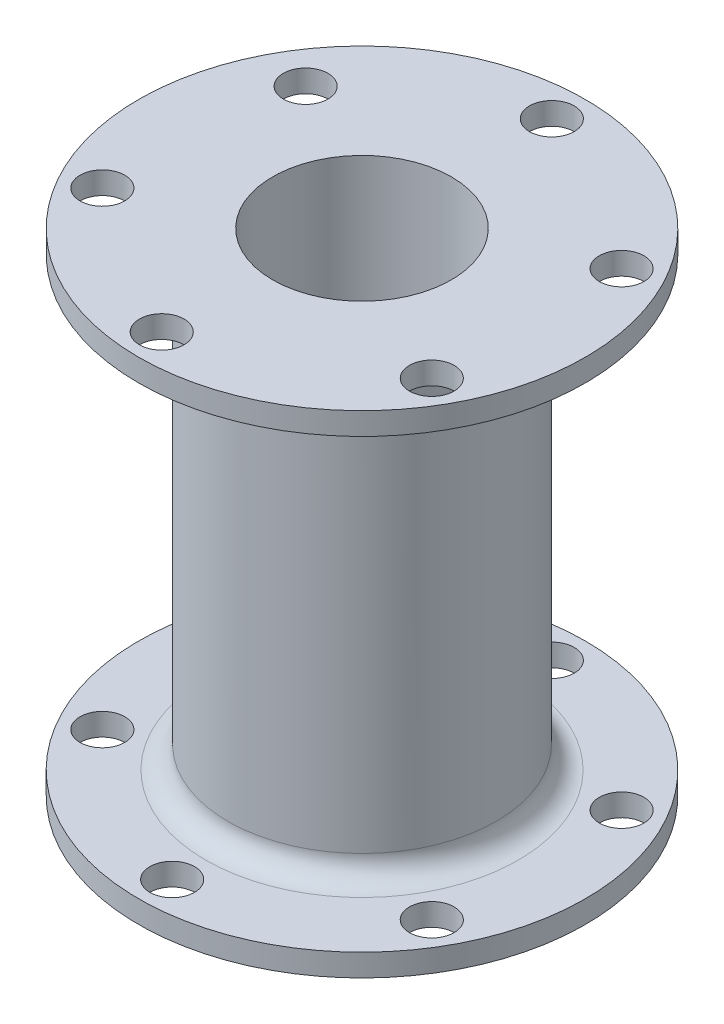
SolidWorks part; units mm, degrees
ref_plane "Front Plane" through (0, 0, 0) normal (0, 0, 1) x (1, 0, 0)
ref_plane "Top Plane" through (0, 0, 0) normal (0, 1, 0) x (1, 0, 0)
ref_plane "Right Plane" through (0, 0, 0) normal (1, 0, 0) x (0, 0, -1)
sketch "Sketch1" plane through (0, 0, 0) normal (0, 1, 0) x (1, 0, 0)
  circle A0 centre (0, 0) radius 127
  circle A1 centre (0, 0) radius 50.8
extrude "Boss-Extrude1" add sketch "Sketch1" along normal blind 12.7 contours A0 | A1
sketch "Sketch2" plane through (0, 12.7, 0) normal (0, 1, 0) x (1, 0, 0)
  circle A0 centre (0, 107.95) radius 12.7
  circle A2 centre (-5.9323, -107.95) radius 12.7
  circle A3 centre (-86.0203, 53.975) radius 12.7
  circle A4 centre (-93.6625, -53.975) radius 12.7
  circle A5 centre (93.6625, -53.975) radius 12.7
  circle A6 centre (93.6625, 53.975) radius 12.7
  dimension "D1" = 25.4
  dimension "D2" = 25.4
  dimension "D4" = 107.95
  dimension "D5" = 53.975
  dimension "D8" = 53.975
  dimension "D9" = 86.0203
  dimension "D10" = 93.6625
  dimension "D3" = 107.95
  dimension "D6" = 53.975
  dimension "D7" = 53.975
  dimension "D11" = 93.6625
  dimension "D12" = 93.6625
extrude "Cut-Extrude1" cut sketch "Sketch2" against normal blind 12.7
sketch "Sketch3" plane through (0, 0, 0) normal (0, -1, 0) x (1, 0, 0)
  circle A0 centre (0, 0) radius 76.2
extrude "Boss-Extrude2" add sketch "Sketch3" along normal blind 254
fillet "Fillet1" radius 12.7 1 edges at (0, 0, 76.2)
sketch "Sketch4" plane through (0, 0, 0) normal (0, 1, 0) x (1, 0, 0)
  circle A0 centre (0, 0) radius 50.8
extrude "Cut-Extrude2" cut sketch "Sketch4" against normal blind 254
sketch "Sketch5" plane through (0, -254, 0) normal (0, -1, 0) x (1, 0, 0)
  circle A0 centre (0, 0) radius 127
extrude "Boss-Extrude3" add sketch "Sketch5" along normal blind 12.7
sketch "Sketch6" plane through (0, -266.7, 0) normal (0, -1, 0) x (1, 0, 0)
  circle A0 centre (0, 0) radius 50.8
extrude "Cut-Extrude3" cut sketch "Sketch6" against normal blind 12.7
sketch "Sketch7" plane through (0, -266.7, 0) normal (0, -1, 0) x (-1, 0, 0)
  circle A0 centre (0, -107.95) radius 12.7
  circle A1 centre (0, 107.95) radius 12.7
  circle A2 centre (-93.6625, 53.975) radius 12.7
  circle A3 centre (-93.6625, -53.975) radius 12.7
  circle A4 centre (93.6625, -53.975) radius 12.7
  circle A5 centre (93.6625, 53.975) radius 12.7
  dimension "D1" = 107.95
  dimension "D2" = 107.95
  dimension "D3" = 53.975
  dimension "D4" = 53.975
  dimension "D5" = 53.975
  dimension "D10" = 93.6625
  dimension "D6" = 53.975
  dimension "D7" = 93.6625
  dimension "D8" = 93.6625
  dimension "D9" = 93.6625
extrude "Cut-Extrude4" cut sketch "Sketch7" against normal blind 12.7
fillet "Fillet2" radius 12.7 1 edges at (0, -254, -76.2)
